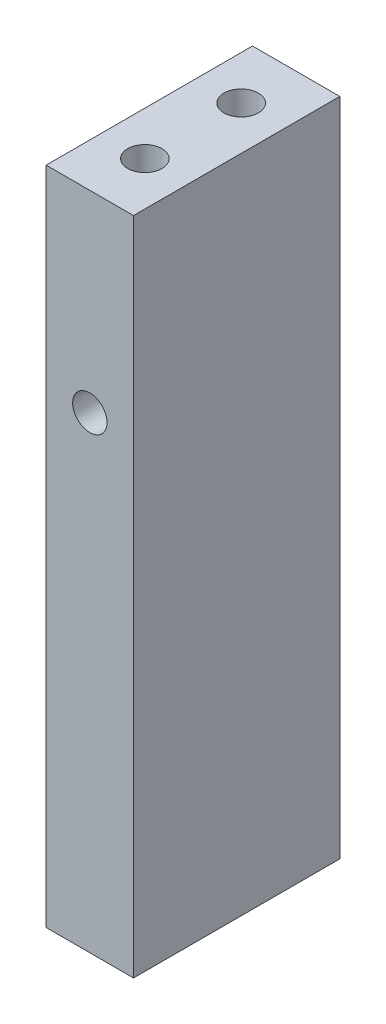
SolidWorks part; units mm, degrees
material "Liga 1060"
ref_plane "Plano frontal" through (0, 0, 0) normal (0, 0, 1) x (1, 0, 0)
ref_plane "Plano superior" through (0, 0, 0) normal (0, 1, 0) x (1, 0, 0)
ref_plane "Plano direito" through (0, 0, 0) normal (1, 0, 0) x (0, 0, -1)
sketch "Esboço1" plane through (0, 0, 0) normal (0, 0, 1) x (1, 0, 0)
  line L1 (0, 0) -> (6.35, 0)
  line L2 (0, 0) -> (0, 48)
  line L3 (0, 48) -> (6.35, 48)
  line L4 (6.35, 0) -> (6.35, 48)
  dimension "D1" = 48
  dimension "D2" = 6.35
extrude "Ressalto-extrusão1" add sketch "Esboço1" along normal blind 15
sketch "Esboço2" plane through (0, 0, 0) normal (0, -1, 0) x (-1, 0, 0)
  line L0 (-3.175, -15) -> (-3.175, 0) construction
  line L1 (0, 0) -> (-6.35, 0) construction
  line L2 (0, 0) -> (0, -15) construction
  line L3 (0, -15) -> (-6.35, -15) construction
  line L4 (-6.35, 0) -> (-6.35, -15) construction
  point P8 (-3.175, -11)
  point P9 (-3.175, -4)
  point P12 (-3.175, -9)
  dimension "D1" = 4
  dimension "D2" = 4
hole_wizard "Furo roscado de M31" positions "3DSketch1" profile "Esboço3" tap size "M3" standard "ISO"
sketch3d "3DSketch1"
  point P0 (3.175, 0, 11)
  point P3 (3.175, 0, 4)
sketch "Esboço3" plane through (3.175, 0, 11) normal (1, 0, 0) x (0, 0, -1)
  line L0 (0, 0) -> (0, 10.7511)
  line L1 (0, 10.7511) -> (1.25, 10)
  line L2 (1.25, 10) -> (1.25, 0)
  line L5 (1.25, 0) -> (0, 0)
  line L10 (0, 10.7511) -> (-1.25, 10) construction
  line L11 (0, -6.35) -> (0, 107.95) construction
  dimension "Tap Drill Dia." = 2.5
  dimension "Tap Drill Depth" = 10
  dimension "Drill Angle" = 118
cosmetic thread "Rosca de furo3" parameters "D1"=9.55, "D2"=3
cosmetic thread "Rosca de furo4" parameters "D1"=9.55, "D2"=3
sketch "Esboço4" plane through (0, 0, 15) normal (0, 0, 1) x (1, 0, 0)
  line L0 (3.175, 48) -> (3.175, 0) construction
  line L1 (6.35, 48) -> (0, 48) construction
  point P5 (3.175, 34)
  point P6 (3.175, 28)
  dimension "D1" = 14
  dimension "D2" = 6
sketch "Esboço5" plane through (0, 48, 0) normal (0, 1, 0) x (1, 0, 0)
  line L0 (3.175, 0) -> (3.175, -15) construction
  point P4 (3.175, -4)
  point P5 (3.175, -11)
hole_wizard "Furo roscado de M32" positions "3DSketch3" profile "Esboço7" tap size "M3" standard "ISO"
sketch3d "3DSketch3"
  point P0 (3.175, 48, 4)
  point P3 (3.175, 48, 11)
sketch "Esboço7" plane through (3.175, 48, 4) normal (1, 0, 0) x (0, 0, 1)
  line L0 (0, 0) -> (0, 10.7511)
  line L1 (0, 10.7511) -> (1.25, 10)
  line L2 (1.25, 10) -> (1.25, 0)
  line L5 (1.25, 0) -> (0, 0)
  line L10 (0, 10.7511) -> (-1.25, 10) construction
  line L11 (0, -6.35) -> (0, 107.95) construction
  dimension "Tap Drill Dia." = 2.5
  dimension "Tap Drill Depth" = 10
  dimension "Drill Angle" = 118
cosmetic thread "Rosca de furo5" parameters "D1"=10, "D2"=3
cosmetic thread "Rosca de furo6" parameters "D1"=10, "D2"=3
hole_wizard "Furo roscado de M33" positions "3DSketch4" profile "Esboço8" tap size "M3" standard "ISO"
sketch3d "3DSketch4"
  point P0 (3.175, 34, 15)
sketch "Esboço8" plane through (3.175, 34, 15) normal (1, 0, 0) x (0, -1, 0)
  line L0 (0, 0) -> (0, 10.7511)
  line L1 (0, 10.7511) -> (1.25, 10)
  line L2 (1.25, 10) -> (1.25, 0)
  line L5 (1.25, 0) -> (0, 0)
  line L10 (0, 10.7511) -> (-1.25, 10) construction
  line L11 (0, -6.35) -> (0, 107.95) construction
  dimension "Tap Drill Dia." = 2.5
  dimension "Tap Drill Depth" = 10
  dimension "Drill Angle" = 118
cosmetic thread "Rosca de furo8" parameters "D1"=9.55, "D2"=3
